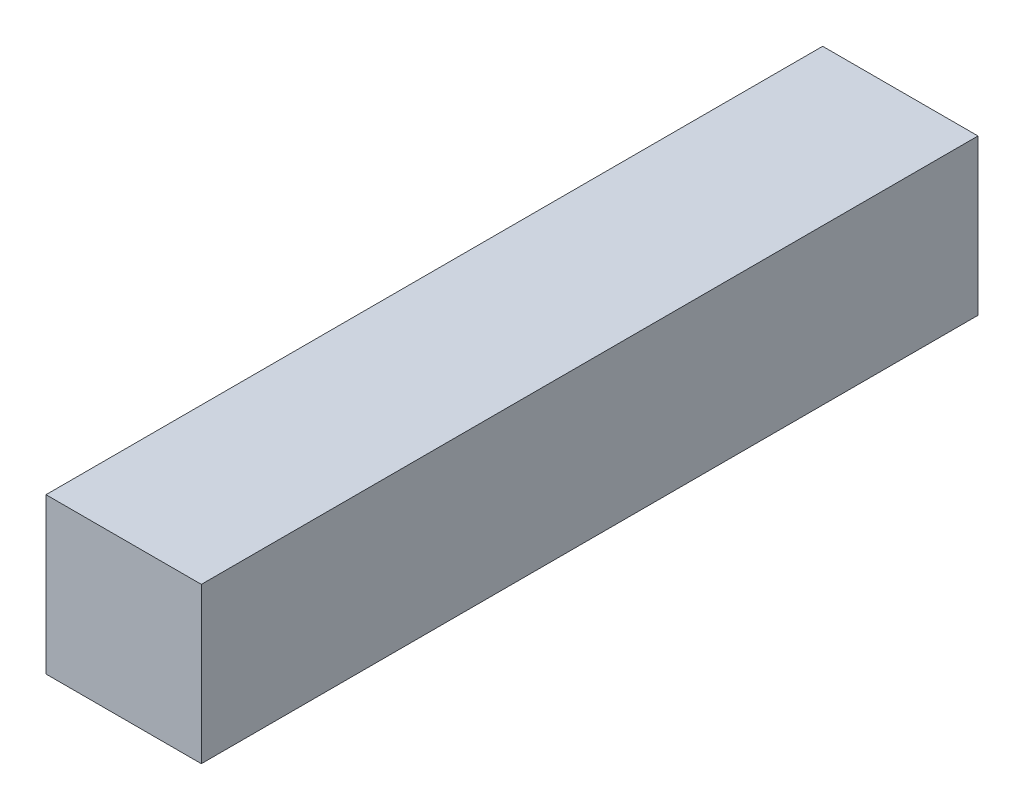
SolidWorks part; units mm, degrees
material "Brass"
ref_plane "Front Plane" through (0, 0, 0) normal (0, 0, 1) x (1, 0, 0)
ref_plane "Top Plane" through (0, 0, 0) normal (0, 1, 0) x (1, 0, 0)
ref_plane "Right Plane" through (0, 0, 0) normal (1, 0, 0) x (0, 0, -1)
sketch "Sketch3" plane through (0, 0, 0) normal (0, 0, 1) x (1, 0, 0)
  line L5 (-50, -50) -> (50, -50)
  line L6 (-50, -50) -> (-50, 50)
  line L7 (-50, 50) -> (50, 50)
  line L8 (50, -50) -> (50, 50)
  line L9 (-50, -50) -> (50, 50) construction
  line L10 (-50, 50) -> (50, -50) construction
  point P0 (0, 0)
  dimension "D1" = 100
  dimension "D2" = 100
extrude "Boss-Extrude1" add sketch "Sketch3" along normal blind 500
